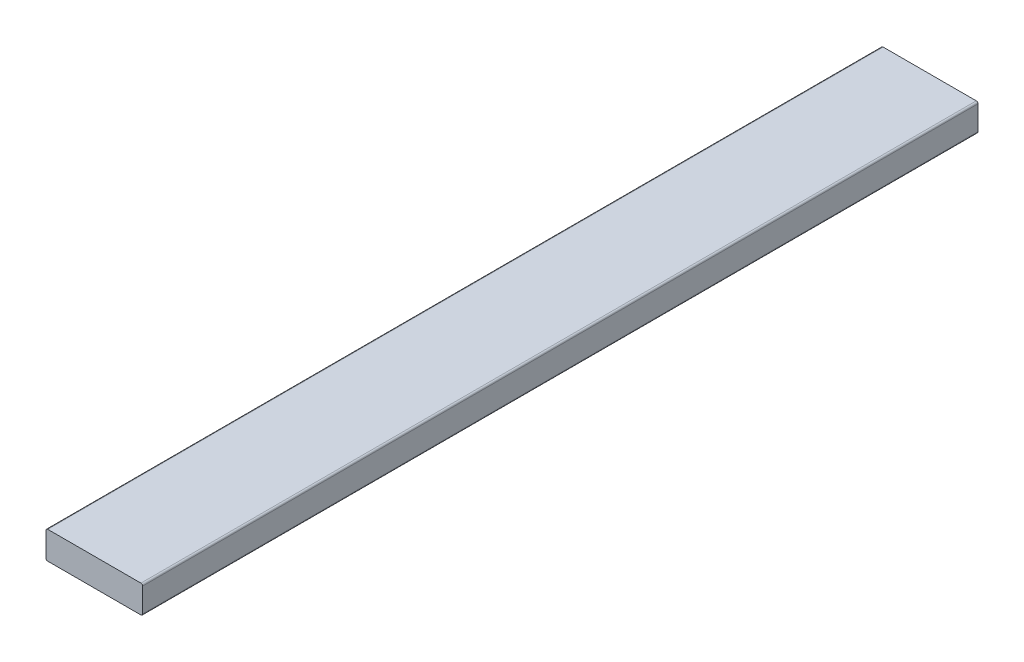
SolidWorks part; units mm, degrees
material "Cedar"
ref_plane "Front Plane" through (0, 0, 0) normal (0, 0, 1) x (1, 0, 0)
ref_plane "Top Plane" through (0, 0, 0) normal (0, 1, 0) x (1, 0, 0)
ref_plane "Right Plane" through (0, 0, 0) normal (1, 0, 0) x (0, 0, -1)
sketch "Sketch1" plane through (0, 0, 0) normal (0, 0, 1) x (1, 0, 0)
  line L1 (-44.45, -12.7) -> (44.45, -12.7)
  line L2 (-44.45, -12.7) -> (-44.45, 12.7)
  line L3 (-44.45, 12.7) -> (44.45, 12.7)
  line L4 (44.45, -12.7) -> (44.45, 12.7)
  line L5 (-44.45, -12.7) -> (44.45, 12.7) construction
  line L6 (-44.45, 12.7) -> (44.45, -12.7) construction
  point P0 (0, 0)
  dimension "D1" = 88.9
  dimension "D2" = 25.4
extrude "Boss-Extrude1" add sketch "Sketch1" along normal blind 768.35
fillet "Fillet1" radius 1.5875 4 edges at (-44.45, -12.7, 384.175) (44.45, -12.7, 384.175) (-44.45, 12.7, 384.175) (44.45, 12.7, 384.175)
